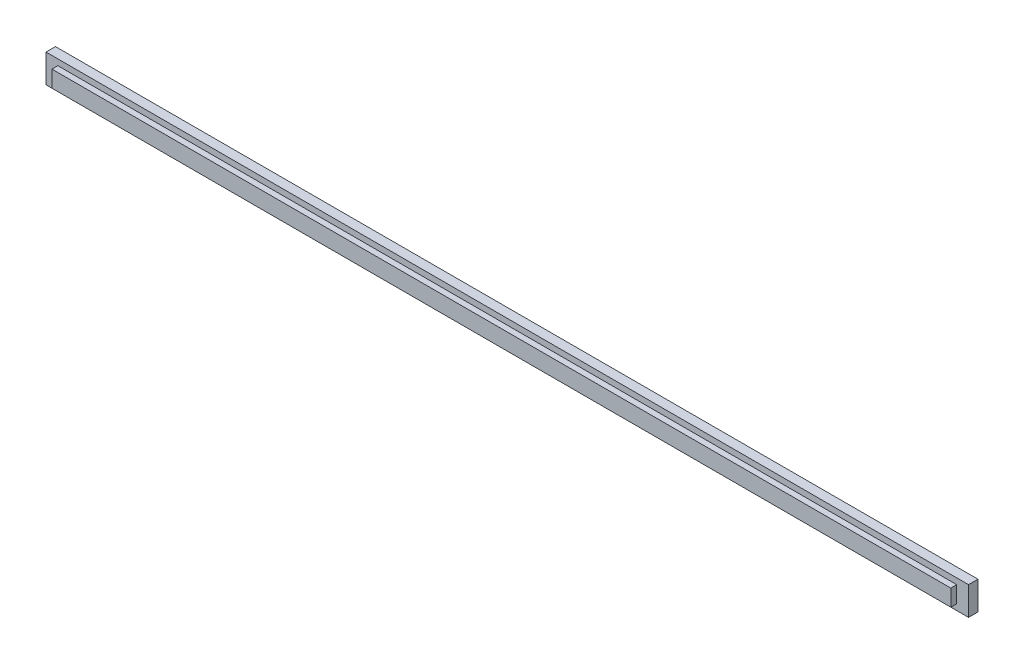
SolidWorks part; units mm, degrees
ref_plane "Plan de face" through (0, 0, 0) normal (0, 0, 1) x (1, 0, 0)
ref_plane "Plan de dessus" through (0, 0, 0) normal (0, 1, 0) x (1, 0, 0)
ref_plane "Plan de droite" through (0, 0, 0) normal (1, 0, 0) x (0, 0, -1)
sketch "Esquisse1" plane through (0, 0, 0) normal (0, 0, 1) x (1, 0, 0)
  line L1 (-195, -6) -> (195, -6)
  line L2 (-195, -6) -> (-195, 6)
  line L3 (-195, 6) -> (195, 6)
  line L4 (195, -6) -> (195, 6)
extrude "Profil_bandeau_LED" add sketch "Esquisse1" along normal blind 4
sketch "Esquisse2" plane through (0, 0, 0) normal (0, 0, 1) x (1, 0, 0)
  line L1 (-190, -3.5) -> (190, -3.5)
  line L2 (-190, -3.5) -> (-190, 3.5)
  line L3 (-190, 3.5) -> (190, 3.5)
  line L4 (190, -3.5) -> (190, 3.5)
extrude "Diffuseur_LED" add sketch "Esquisse2" along normal blind 2.5 from offset 4
